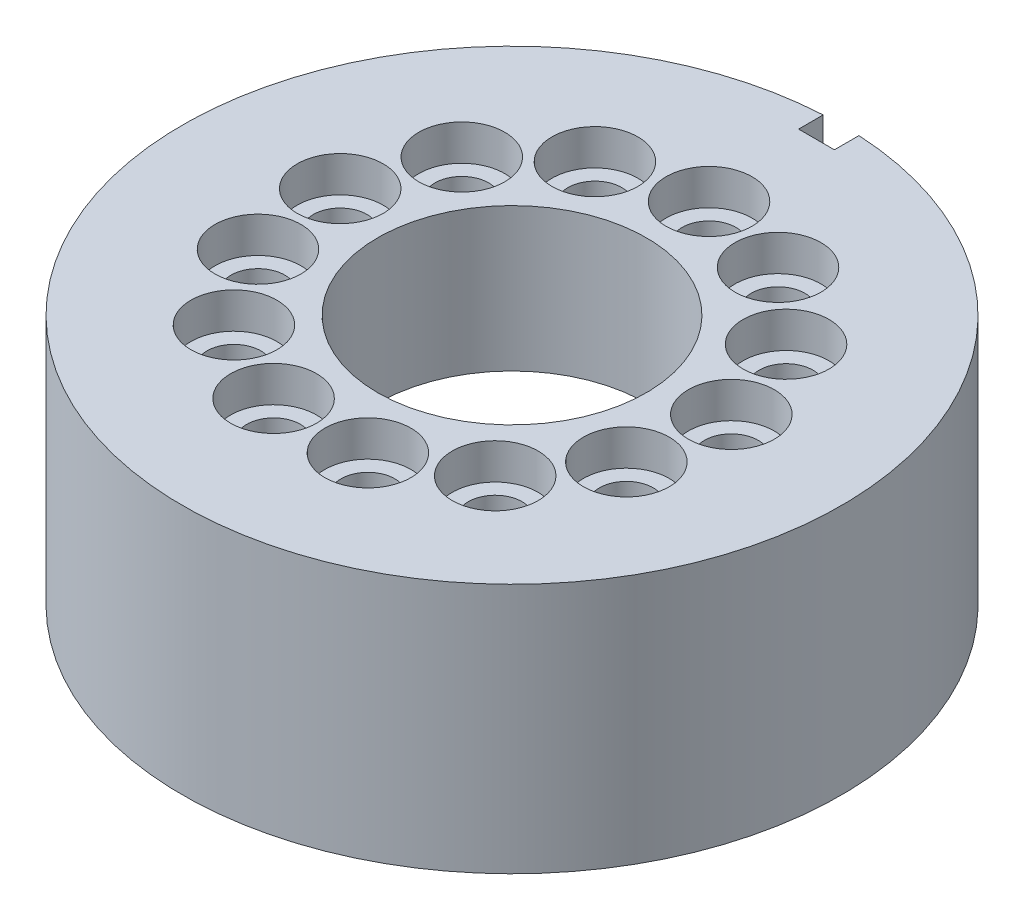
SolidWorks part; units mm, degrees
ref_plane "前视基准面" through (0, 0, 0) normal (0, 0, 1) x (1, 0, 0)
ref_plane "上视基准面" through (0, 0, 0) normal (0, 1, 0) x (1, 0, 0)
ref_plane "右视基准面" through (0, 0, 0) normal (1, 0, 0) x (0, 0, -1)
sketch "草图1" plane through (0, 0, 0) normal (0, 1, 0) x (1, 0, 0)
  circle A0 centre (0, 0) radius 5.5 construction
  circle A1 centre (0, 5.5) radius 0.75
  circle A2 centre (2.556, 4.87) radius 0.75
  circle A3 centre (4.5264, 3.1244) radius 0.75
  circle A4 centre (5.4599, 0.663) radius 0.75
  circle A5 centre (5.1426, -1.9503) radius 0.75
  circle A6 centre (3.6472, -4.1168) radius 0.75
  circle A7 centre (1.3162, -5.3402) radius 0.75
  circle A8 centre (-1.3162, -5.3402) radius 0.75
  circle A9 centre (-3.6472, -4.1168) radius 0.75
  circle A10 centre (-5.1426, -1.9503) radius 0.75
  circle A11 centre (-5.4599, 0.663) radius 0.75
  circle A12 centre (-4.5264, 3.1244) radius 0.75
  circle A13 centre (-2.556, 4.87) radius 0.75
  circle A14 centre (0, 0) radius 9.2
  point P32 (0, 0)
  dimension "D1" = 11
  dimension "D2" = 1.5
  dimension "D4" = 18.4
  dimension "D3" = 13
extrude "凸台-拉伸1" add sketch "草图1" along normal blind 7
sketch "草图2" plane through (0, 7, 0) normal (0, 1, 0) x (1, 0, 0)
  line L0 (-0.5, 9.2981) -> (0.5, 9.2981)
  line L1 (0.5, 9.2981) -> (0.5, 8.5)
  line L2 (0.5, 8.5) -> (-0.5, 8.5)
  line L3 (-0.5, 8.5) -> (-0.5, 9.2981)
  point P2 (0, 8.5)
  dimension "D1" = 1
  dimension "D2" = 8.5
extrude "切除-拉伸1" cut sketch "草图2" against normal blind 7.5
sketch "草图5" plane through (0, 0, 0) normal (1, 0, 0) x (0, 0, -1)
  line L0 (-6, 3) -> (0, 3)
  line L1 (0, 3) -> (0, 0)
  line L2 (0, 0) -> (-9, 0)
  spline S0 degree 3 poles (-9, 0) (-8.3845, 1.2959) (-7.5122, 2.6322) (-6, 3) knots 0 0 0 0 1 1 1 1
  point P1 (-7.8549, 1.7242)
  point P3 (-7.5542, 2.1376)
  point P4 (-8.569, 0.8222)
  point P8 (0, 0)
  point P11 (-9.0048, 0)
  dimension "D1" = 6
  dimension "D2" = 3
  dimension "D3" = 0.2
revolve "切除-旋转1" cut sketch "草图5" angle 360 about L1
sketch "草图6" plane through (0, 7, 0) normal (0, 1, 0) x (1, 0, 0)
  circle A0 centre (0, 0) radius 3.75
  dimension "D1" = 7.5
extrude "切除-拉伸3" cut sketch "草图6" against normal blind 5
sketch "草图7" plane through (0, 7, 0) normal (0, 1, 0) x (1, 0, 0)
  circle A0 centre (0, 5.5) radius 1.2
  circle A1 centre (2.556, 4.87) radius 1.2
  circle A2 centre (4.5264, 3.1244) radius 1.2
  circle A3 centre (5.4599, 0.663) radius 1.2
  circle A4 centre (5.1426, -1.9503) radius 1.2
  circle A5 centre (3.6472, -4.1168) radius 1.2
  circle A6 centre (1.3162, -5.3402) radius 1.2
  circle A7 centre (-1.3162, -5.3402) radius 1.2
  circle A8 centre (-3.6472, -4.1168) radius 1.2
  circle A9 centre (-5.1426, -1.9503) radius 1.2
  circle A10 centre (-5.4599, 0.663) radius 1.2
  circle A11 centre (-4.5264, 3.1244) radius 1.2
  circle A12 centre (-2.556, 4.87) radius 1.2
  point P29 (0, 0)
  dimension "D1" = 2.4
  dimension "D2" = 13
extrude "切除-拉伸4" cut sketch "草图7" against normal blind 1
